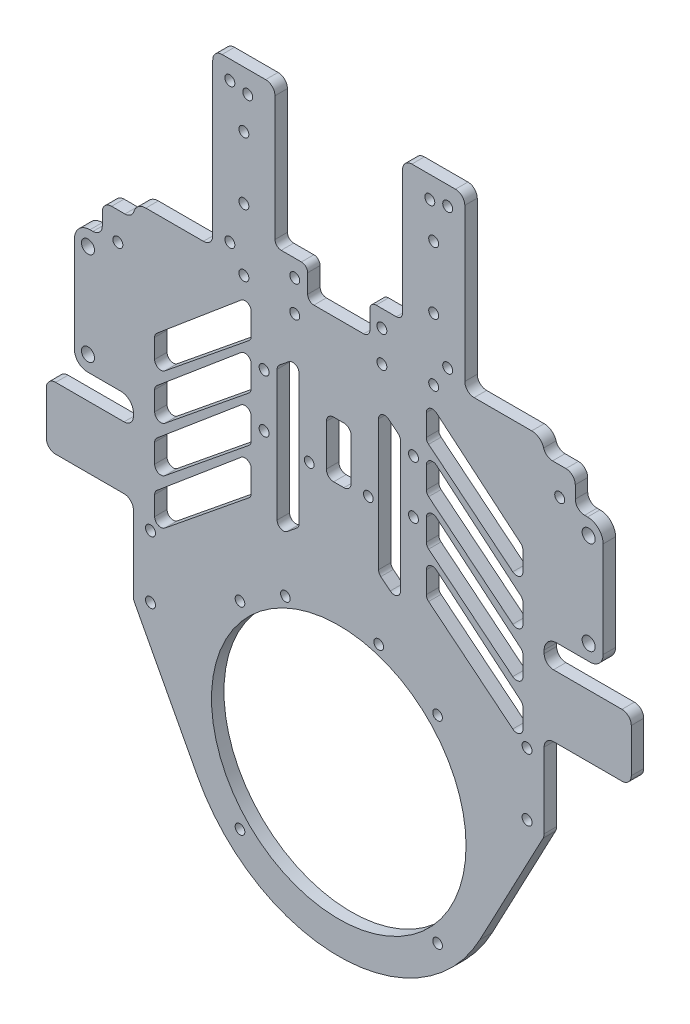
SolidWorks part; units mm, degrees
material "Thornel Mat VMA"
ref_plane "前视基准面" through (0, 0, 0) normal (0, 0, 1) x (1, 0, 0)
ref_plane "上视基准面" through (0, 0, 0) normal (0, 1, 0) x (1, 0, 0)
ref_plane "右视基准面" through (0, 0, 0) normal (1, 0, 0) x (0, 0, -1)
sketch "草图1" plane through (0, 0, 0) normal (0, 0, 1) x (1, 0, 0)
  line L0 (-66, 126) -> (66, 126)
  line L1 (66, 126) -> (66, 15.1)
  line L2 (66, 15.1) -> (45.3153, -23.9831)
  line L3 (-45.3153, -23.9831) -> (-66, 15.1)
  line L4 (-66, 15.1) -> (-66, 126)
  line L5 (0, 143.651) -> (0, -77.7988) construction
  line L6 (-17.1531, 40.4102) -> (0, 0) construction
  line L7 (0, 0) -> (12.8351, 41.9818) construction
  line L8 (-31.7491, 31.7491) -> (0, 0) construction
  line L9 (-24.2152, 81.5) -> (25.2173, 81.5) construction
  line L10 (-29.945, 120.5) -> (27.106, 120.5) construction
  arc A0 (45.3153, -23.9831) -> (-45.3153, -23.9831) centre (0, 0) cw
  circle A1 centre (0, 0) radius 40.9
  circle A2 centre (0, 0) radius 44.9 construction
  circle A3 centre (-31.7491, 31.7491) radius 1.55
  circle A4 centre (-17.1531, 40.4102) radius 1.55
  circle A5 centre (12.8351, 41.9818) radius 1.55
  circle A6 centre (31.7491, 31.7491) radius 1.55
  circle A7 centre (31.7491, -31.7491) radius 1.55
  circle A8 centre (-31.7491, -31.7491) radius 1.55
  circle A9 centre (-9.5, 81.5) radius 1.55
  circle A10 centre (9.5, 81.5) radius 1.55
  circle A11 centre (-14.15, 120.5) radius 1.6
  circle A12 centre (13.85, 120.5) radius 1.6
  point P27 (0, 0)
  dimension "D3" = 81.8
  dimension "D4" = 89.8
  dimension "D7" = 17
  dimension "D11" = 3.1
  dimension "D14" = 63.4982
  dimension "D15" = 44.9
  dimension "D17" = 9.5
  dimension "D20" = 3.2
  dimension "D21" = 14.15
  dimension "D1" = 132
  dimension "D2" = 110.9
  dimension "D5" = 126
  dimension "D6" = 152.11
  dimension "D8" = 40
  dimension "D9" = 43.9
  dimension "D10" = 43.9
  dimension "D13" = 45
  dimension "D16" = 81.5
  dimension "D18" = 9.5
  dimension "D19" = 5.5
  dimension "D22" = 13.85
  dimension "D12" = 4
extrude "凸台-拉伸1" add sketch "草图1" along normal blind 4
sketch "草图2" plane through (0, 0, 4) normal (0, 0, 1) x (1, 0, 0)
  line L0 (-66, 111) -> (-79.95, 111)
  line L1 (-66, 126) -> (-66, 15.1) construction
  line L2 (-84.95, 106) -> (-84.95, 75.2)
  line L3 (-80.75, 71) -> (-66, 71)
  line L4 (-66, 71) -> (-66, 111)
  line L5 (0, 118.3019) -> (0, -51.4362) construction
  line L6 (66, 126) -> (-66, 126) construction
  line L7 (66, 71) -> (66, 111)
  line L8 (80.75, 71) -> (66, 71)
  line L9 (84.95, 106) -> (84.95, 75.2)
  line L10 (66, 111) -> (79.95, 111)
  circle A0 centre (-80.6, 106) radius 2.1
  circle A1 centre (-80.6, 76) radius 2.1
  arc A2 (-84.95, 106) -> (-79.95, 111) centre (-79.95, 106) cw
  arc A3 (-84.95, 75.2) -> (-80.75, 71) centre (-80.75, 75.2) ccw
  arc A4 (84.95, 75.2) -> (80.75, 71) centre (80.75, 75.2) cw
  arc A5 (84.95, 106) -> (79.95, 111) centre (79.95, 106) ccw
  circle A6 centre (80.3, 76) radius 2.1
  circle A7 centre (80.3, 106) radius 2.1
  point P18 (-84.95, 111)
  point P21 (-84.95, 71)
  point P34 (84.95, 71)
  point P35 (84.95, 111)
  dimension "D3" = 4.2
  dimension "D6" = 4.35
  dimension "D9" = 5
  dimension "D10" = 4.2
  dimension "D4" = 30
  dimension "D8" = 4.35
  dimension "D12" = 30
  dimension "D13" = 5
  dimension "D14" = 4.2
  dimension "D15" = 4.2
  dimension "D16" = 4.65
  dimension "D17" = 4.65
  dimension "D2" = 40
  dimension "D5" = 5
  dimension "D7" = 15
  dimension "D11" = 169.9
extrude "凸台-拉伸2" add sketch "草图2" against normal blind 4
sketch "草图3" plane through (0, 0, 4) normal (0, 0, 1) x (1, 0, 0)
  line L0 (0, 115.5232) -> (0, -53.75) construction
  line L13 (-4, 95.6433) -> (-4, 82.3567)
  line L14 (-1.6433, 80) -> (1.6433, 80)
  line L15 (4, 82.3567) -> (4, 95.6433)
  line L16 (1.6433, 98) -> (-1.6433, 98)
  line L32 (84.95, 75.2) -> (84.95, 106) construction
  line L33 (66, 126) -> (-66, 126) construction
  line L40 (-31.4189, 115.6719) -> (-58.4619, 92.9442)
  line L41 (-59.1752, 91.4131) -> (-59.1752, 85.2814)
  line L42 (-55.9148, 83.7285) -> (-28.8718, 105.6783)
  line L43 (-28.1322, 107.2311) -> (-28.1322, 114.1408)
  line L44 (-28.1322, 92.6485) -> (-28.1322, 99.5581)
  line L45 (-31.4189, 101.0892) -> (-58.4619, 78.3615)
  line L46 (-55.9148, 69.1458) -> (-28.8718, 91.0956)
  line L47 (-59.1752, 76.8304) -> (-59.1752, 70.6987)
  line L48 (-28.1322, 78.0658) -> (-28.1322, 84.9755)
  line L49 (-31.4189, 86.5065) -> (-58.4619, 63.7788)
  line L50 (-55.9148, 54.5632) -> (-28.8718, 76.5129)
  line L51 (-59.1752, 62.2477) -> (-59.1752, 56.116)
  line L52 (-28.1322, 63.4831) -> (-28.1322, 70.3928)
  line L53 (-31.4189, 71.9239) -> (-58.4619, 49.1961)
  line L54 (-55.9148, 39.9805) -> (-28.8718, 61.9302)
  line L55 (-59.1752, 47.665) -> (-59.1752, 41.5333)
  line L56 (-16.0321, 106.2463) -> (-19.0746, 103.7769)
  line L57 (-19.8142, 102.224) -> (-19.8142, 60.2677)
  line L58 (-16.5538, 58.7148) -> (-13.5113, 61.1843)
  line L59 (-12.7717, 62.7371) -> (-12.7717, 104.6934)
  line L60 (12.7717, 62.7371) -> (12.7717, 104.6934)
  line L61 (16.5538, 58.7148) -> (13.5113, 61.1843)
  line L62 (19.8142, 102.224) -> (19.8142, 60.2677)
  line L63 (16.0321, 106.2463) -> (19.0746, 103.7769)
  line L64 (59.1752, 47.665) -> (59.1752, 41.5333)
  line L65 (55.9148, 39.9805) -> (28.8718, 61.9302)
  line L66 (31.4189, 71.9239) -> (58.4619, 49.1961)
  line L67 (28.1322, 63.4831) -> (28.1322, 70.3928)
  line L68 (59.1752, 62.2477) -> (59.1752, 56.116)
  line L69 (55.9148, 54.5632) -> (28.8718, 76.5129)
  line L70 (31.4189, 86.5065) -> (58.4619, 63.7788)
  line L71 (28.1322, 78.0658) -> (28.1322, 84.9755)
  line L72 (59.1752, 76.8304) -> (59.1752, 70.6987)
  line L73 (55.9148, 69.1458) -> (28.8718, 91.0956)
  line L74 (31.4189, 101.0892) -> (58.4619, 78.3615)
  line L75 (28.1322, 92.6485) -> (28.1322, 99.5581)
  line L76 (28.1322, 107.2311) -> (28.1322, 114.1408)
  line L77 (55.9148, 83.7285) -> (28.8718, 105.6783)
  line L78 (59.1752, 91.4131) -> (59.1752, 85.2814)
  line L79 (31.4189, 115.6719) -> (58.4619, 92.9442)
  circle A9 centre (0, 0) radius 40.9 construction
  arc A10 (4, 95.6433) -> (1.6433, 98) centre (1.6433, 95.6433) ccw
  arc A11 (4, 82.3567) -> (1.6433, 80) centre (1.6433, 82.3567) cw
  arc A12 (-1.6433, 80) -> (-4, 82.3567) centre (-1.6433, 82.3567) cw
  arc A13 (-4, 95.6433) -> (-1.6433, 98) centre (-1.6433, 95.6433) cw
  arc A35 (-16.0321, 106.2463) -> (-12.7717, 104.6934) centre (-14.7717, 104.6934) cw
  arc A36 (-19.0746, 103.7769) -> (-19.8142, 102.224) centre (-17.8142, 102.224) ccw
  arc A37 (-13.5113, 61.1843) -> (-12.7717, 62.7371) centre (-14.7717, 62.7371) ccw
  arc A38 (-19.8142, 60.2677) -> (-16.5538, 58.7148) centre (-17.8142, 60.2677) ccw
  arc A39 (-55.9148, 39.9805) -> (-59.1752, 41.5333) centre (-57.1752, 41.5333) cw
  arc A40 (-58.4619, 49.1961) -> (-59.1752, 47.665) centre (-57.1752, 47.665) ccw
  arc A41 (-28.1322, 63.4831) -> (-28.8718, 61.9302) centre (-30.1322, 63.4831) cw
  arc A42 (-28.1322, 70.3928) -> (-31.4189, 71.9239) centre (-30.1322, 70.3928) ccw
  arc A43 (-55.9148, 54.5632) -> (-59.1752, 56.116) centre (-57.1752, 56.116) cw
  arc A44 (-58.4619, 63.7788) -> (-59.1752, 62.2477) centre (-57.1752, 62.2477) ccw
  arc A45 (-28.1322, 78.0658) -> (-28.8718, 76.5129) centre (-30.1322, 78.0658) cw
  arc A46 (-28.1322, 84.9755) -> (-31.4189, 86.5065) centre (-30.1322, 84.9755) ccw
  arc A47 (-58.4619, 78.3615) -> (-59.1752, 76.8304) centre (-57.1752, 76.8304) ccw
  arc A48 (-55.9148, 69.1458) -> (-59.1752, 70.6987) centre (-57.1752, 70.6987) cw
  arc A49 (-28.1322, 92.6485) -> (-28.8718, 91.0956) centre (-30.1322, 92.6485) cw
  arc A50 (-28.1322, 99.5581) -> (-31.4189, 101.0892) centre (-30.1322, 99.5581) ccw
  arc A51 (-59.1752, 85.2814) -> (-55.9148, 83.7285) centre (-57.1752, 85.2814) ccw
  arc A52 (-58.4619, 92.9442) -> (-59.1752, 91.4131) centre (-57.1752, 91.4131) ccw
  arc A53 (-28.8718, 105.6783) -> (-28.1322, 107.2311) centre (-30.1322, 107.2311) ccw
  arc A54 (-31.4189, 115.6719) -> (-28.1322, 114.1408) centre (-30.1322, 114.1408) cw
  arc A55 (31.4189, 115.6719) -> (28.1322, 114.1408) centre (30.1322, 114.1408) ccw
  arc A56 (28.8718, 105.6783) -> (28.1322, 107.2311) centre (30.1322, 107.2311) cw
  arc A57 (58.4619, 92.9442) -> (59.1752, 91.4131) centre (57.1752, 91.4131) cw
  arc A58 (59.1752, 85.2814) -> (55.9148, 83.7285) centre (57.1752, 85.2814) cw
  arc A59 (28.1322, 99.5581) -> (31.4189, 101.0892) centre (30.1322, 99.5581) cw
  arc A60 (28.1322, 92.6485) -> (28.8718, 91.0956) centre (30.1322, 92.6485) ccw
  arc A61 (55.9148, 69.1458) -> (59.1752, 70.6987) centre (57.1752, 70.6987) ccw
  arc A62 (58.4619, 78.3615) -> (59.1752, 76.8304) centre (57.1752, 76.8304) cw
  arc A63 (28.1322, 84.9755) -> (31.4189, 86.5065) centre (30.1322, 84.9755) cw
  arc A64 (28.1322, 78.0658) -> (28.8718, 76.5129) centre (30.1322, 78.0658) ccw
  arc A65 (58.4619, 63.7788) -> (59.1752, 62.2477) centre (57.1752, 62.2477) cw
  arc A66 (55.9148, 54.5632) -> (59.1752, 56.116) centre (57.1752, 56.116) ccw
  arc A67 (28.1322, 70.3928) -> (31.4189, 71.9239) centre (30.1322, 70.3928) cw
  arc A68 (28.1322, 63.4831) -> (28.8718, 61.9302) centre (30.1322, 63.4831) ccw
  arc A69 (58.4619, 49.1961) -> (59.1752, 47.665) centre (57.1752, 47.665) cw
  arc A70 (55.9148, 39.9805) -> (59.1752, 41.5333) centre (57.1752, 41.5333) ccw
  arc A71 (19.8142, 60.2677) -> (16.5538, 58.7148) centre (17.8142, 60.2677) cw
  arc A72 (13.5113, 61.1843) -> (12.7717, 62.7371) centre (14.7717, 62.7371) cw
  arc A73 (19.0746, 103.7769) -> (19.8142, 102.224) centre (17.8142, 102.224) cw
  arc A74 (16.0321, 106.2463) -> (12.7717, 104.6934) centre (14.7717, 104.6934) ccw
  dimension "D1" = 4
  dimension "D6" = 2.3567
  dimension "D7" = 2
  dimension "D2" = 4
  dimension "D3" = 4
  dimension "D4" = 18
  dimension "D5" = 80
extrude "切除-拉伸1" cut sketch "草图3" against normal blind 4
fillet "圆角1" radius 4 4 edges at (-66, 71, 2) (66, 71, 2) (66, 126, 2) (-66, 126, 2)
sketch "草图4" plane through (0, 0, 4) normal (0, 0, 1) x (1, 0, 0)
  line L0 (-10, 126) -> (-10, 119)
  line L1 (62, 126) -> (-62, 126) construction
  line L2 (-10, 119) -> (10, 119)
  line L3 (10, 119) -> (10, 126)
  line L4 (10, 126) -> (-10, 126)
  line L5 (66, 111) -> (66, 122) construction
  dimension "D1" = 7
  dimension "D2" = 20
  dimension "D3" = 56
extrude "切除-拉伸2" cut sketch "草图4" against normal through all
fillet "圆角2" radius 2 4 edges at (10, 126, 2) (-10, 126, 2) (-10, 119, 2) (10, 119, 2)
sketch "草图5" plane through (0, 0, 4) normal (0, 0, 1) x (1, 0, 0)
  line L0 (-40.5, 126) -> (-40.5, 181)
  line L1 (-12, 126) -> (-62, 126) construction
  line L2 (-40.5, 181) -> (-20.5, 181)
  line L3 (-20.5, 181) -> (-20.5, 126)
  line L4 (-40.5, 126) -> (-20.5, 126)
  line L5 (0, 172.5721) -> (0, 103.5745) construction
  line L10 (20.5, 126) -> (20.5, 181)
  line L11 (62, 126) -> (12, 126) construction
  line L12 (20.5, 181) -> (40.5, 181)
  line L13 (40.5, 181) -> (40.5, 126)
  line L14 (40.5, 126) -> (20.5, 126)
  dimension "D1" = 20
  dimension "D2" = 55
  dimension "D3" = 20.5
  dimension "D4" = 20
  dimension "D5" = 55
  dimension "D6" = 20.5
extrude "凸台-拉伸3" add sketch "草图5" against normal blind 4
sketch "草图6" plane through (0, 0, 4) normal (0, 0, 1) x (1, 0, 0)
  line L0 (-40.5, 181) -> (-40.5, 126) construction
  line L2 (0, 181.9353) -> (0, 128.2449) construction
  line L3 (-20.5, 181) -> (-40.5, 181) construction
  circle A0 centre (-29.75, 177) radius 1.65
  circle A1 centre (-29.75, 143.5) radius 1.65
  circle A4 centre (29.75, 143.5) radius 1.65
  circle A5 centre (29.75, 177) radius 1.65
  dimension "D1" = 3.3
  dimension "D2" = 10.75
  dimension "D4" = 4
  dimension "D3" = 33.5
fillet "圆角3" radius 3 4 edges at (40.5, 126, 2) (40.5, 181, 2) (-40.5, 126, 2) (-40.5, 181, 2)
sketch "草图7" plane through (0, 0, 4) normal (0, 0, 1) x (1, 0, 0)
  line L0 (0, 0) -> (0, 119) construction
  line L1 (-8, 119) -> (8, 119) construction
  line L2 (-30.5, 163) -> (-30.5, 130.7752) construction
  line L5 (-43.5, 126) -> (-62, 126) construction
  circle A0 centre (-30.5, 163) radius 1.6
  circle A1 centre (-30.5, 143) radius 1.6
  circle A2 centre (-30.5, 123) radius 1.6
  circle A3 centre (30.5, 163) radius 1.6
  circle A4 centre (30.5, 123) radius 1.6
  circle A5 centre (30.5, 143) radius 1.6
  dimension "D1" = 3.2
  dimension "D2" = 20
  dimension "D3" = 20
  dimension "D4" = 61
  dimension "D5" = 3
extrude "切除-拉伸4" cut sketch "草图7" against normal blind 10
sketch "草图8" plane through (0, 0, 4) normal (0, 0, 1) x (1, 0, 0)
  line L2 (24, 83) -> (-24, 83) construction
  line L3 (24, 83) -> (24, 100) construction
  line L4 (24, 100) -> (-24, 100) construction
  line L5 (-24, 83) -> (-24, 100) construction
  line L6 (24, 83) -> (-24, 100) construction
  line L7 (24, 100) -> (-24, 83) construction
  line L8 (37.5, 181) -> (20.5, 181) construction
  line L9 (0, 0) -> (0, 123.2843)
  circle A0 centre (-24, 100) radius 1.6
  circle A1 centre (24, 100) radius 1.6
  circle A2 centre (24, 83) radius 1.6
  circle A3 centre (-24, 83) radius 1.6
  point P0 (0, 91.5)
  dimension "D1" = 17
  dimension "D2" = 48
  dimension "D4" = 3.2
  dimension "D3" = 81
extrude "切除-拉伸7" cut sketch "草图8" against normal blind 24 contours A0 | A3 | A2 | A1
sketch "草图9" plane through (0, 0, 4) normal (0, 0, 1) x (1, 0, 0)
  line L0 (0, 0) -> (0, 119) construction
  line L1 (66, 111) -> (76, 111)
  line L2 (66, 111) -> (66, 121)
  line L3 (66, 121) -> (76, 121)
  line L4 (76, 111) -> (76, 121)
  line L5 (-8, 119) -> (8, 119) construction
  line L6 (-66, 121) -> (-76, 121)
  line L7 (-76, 111) -> (-76, 121)
  line L8 (-66, 111) -> (-76, 111)
  line L9 (-66, 111) -> (-66, 121)
  dimension "D1" = 10
  dimension "D2" = 10
extrude "凸台-拉伸4" add sketch "草图9" against normal blind 4
fillet "圆角5" radius 3 6 edges at (-76, 111, 2) (-76, 121, 2) (-66, 121, 2) (66, 121, 2) (76, 121, 2) (76, 111, 2)
sketch "草图10" plane through (0, 0, 4) normal (0, 0, 1) x (1, 0, 0)
  line L0 (-76, 118) -> (-76, 114) construction
  line L1 (-68.7082, 121) -> (-73, 121) construction
  line L2 (0, 0) -> (0, 119) construction
  line L3 (-8, 119) -> (8, 119) construction
  circle A0 centre (-71, 112) radius 1.6
  circle A1 centre (71, 112) radius 1.6
  dimension "D1" = 3.2
  dimension "D2" = 5
  dimension "D3" = 9
extrude "切除-拉伸6" cut sketch "草图10" against normal blind 4
sketch "草图11" plane through (0, 0, 4) normal (0, 0, 1) x (1, 0, 0)
  line L0 (66, 15.1) -> (66, 67) construction
  line L1 (66, 63) -> (94, 63)
  line L2 (66, 63) -> (66, 43)
  line L3 (66, 43) -> (94, 43)
  line L4 (94, 63) -> (94, 43)
  line L5 (70, 71) -> (80.75, 71) construction
  line L6 (0, 27.3868) -> (0, -17.8221) construction
  line L7 (-66, 43) -> (-94, 43)
  line L8 (-66, 63) -> (-66, 43)
  line L9 (-66, 63) -> (-94, 63)
  line L10 (-94, 63) -> (-94, 43)
  dimension "D1" = 20
  dimension "D2" = 28
  dimension "D3" = 8
extrude "凸台-拉伸5" add sketch "草图11" against normal blind 4
fillet "圆角6" radius 3 12 edges at (-20.5, 181, 2) (20.5, 181, 2) (-94, 63, 2) (-94, 43, 2) (-66, 43, 2) (-66, 15.1, 2) (66, 15.1, 2) (66, 43, 2) (94, 43, 2) (94, 63, 2) (66, 63, 2) (-66, 63, 2)
sketch "草图13" plane through (0, 0, 4) normal (0, 0, 1) x (1, 0, 0)
  line L0 (-60.5, 152.6337) -> (-60.5, -37.2841) construction
  line L1 (-66, 40) -> (-66, 15.8449) construction
  line L2 (-91, 43) -> (-69, 43) construction
  line L3 (0, 166.4374) -> (0, -97.031) construction
  circle A0 centre (-60.5, 37) radius 1.6
  circle A1 centre (-60.5, 17) radius 1.6
  circle A2 centre (60.5, 17) radius 1.6
  circle A3 centre (60.5, 37) radius 1.6
  dimension "D2" = 3.2
  dimension "D3" = 20
  dimension "D4" = 6
  dimension "D1" = 5.5
extrude "切除-拉伸8" cut sketch "草图13" against normal blind 45
sketch "草图14" plane through (0, 0, 4) normal (0, 0, 1) x (1, 0, 0)
  line L0 (-23.5, 181) -> (-37.5, 181) construction
  line L1 (-40.5, 178) -> (-40.5, 129) construction
  line L2 (0, 181.7466) -> (0, 80.6903) construction
  circle A0 centre (-29.25, 174) radius 1.6
  circle A1 centre (29.25, 174) radius 1.6
  dimension "D1" = 3.2
  dimension "D2" = 7
  dimension "D3" = 11.25
extrude "切除-拉伸9" cut sketch "草图14" against normal blind 10
sketch "草图15" plane through (0, 0, 4) normal (0, 0, 1) x (1, 0, 0)
  line L0 (0, 152.5) -> (0, 0) construction
  line L1 (35, 130) -> (-35, 130) construction
  line L2 (35, 130) -> (35, 175) construction
  line L3 (35, 175) -> (-35, 175) construction
  line L4 (-35, 130) -> (-35, 175) construction
  line L5 (35, 130) -> (-35, 175) construction
  line L6 (35, 175) -> (-35, 130) construction
  line L7 (-23.5, 181) -> (-37.5, 181) construction
  circle A0 centre (-35, 175) radius 1.6
  circle A1 centre (35, 175) radius 1.6
  circle A2 centre (-35, 130) radius 1.6
  circle A3 centre (35, 130) radius 1.6
  point P0 (0, 152.5)
  dimension "D4" = 3.2
  dimension "D1" = 45
  dimension "D2" = 70
  dimension "D3" = 6
extrude "切除-拉伸10" cut sketch "草图15" against normal blind 10
sketch "草图16" plane through (0, 0, 4) normal (0, 0, 1) x (1, 0, 0)
  line L0 (-20.5, 136) -> (20.5, 136)
  line L1 (-14.15, 130.5) -> (-14.15, 120.5) construction
  line L2 (13.85, 120.5) -> (13.85, 130.5) construction
  line L35 (-20.5, 126) -> (-20.5, 178)
  line L36 (-23.5, 181) -> (-37.5, 181)
  line L37 (-40.5, 178) -> (-40.5, 129)
  line L38 (-43.5, 126) -> (-62, 126)
  line L39 (-68.7082, 121) -> (-73, 121)
  line L40 (-76, 118) -> (-76, 114)
  line L41 (-79, 111) -> (-79.95, 111)
  line L42 (-84.95, 106) -> (-84.95, 75.2)
  line L43 (-80.75, 71) -> (-70, 71)
  line L44 (-66, 67) -> (-66, 66)
  line L45 (-69, 63) -> (-91, 63)
  line L46 (-94, 60) -> (-94, 46)
  line L47 (-91, 43) -> (-69, 43)
  line L48 (-66, 40) -> (-66, 15.8449)
  line L49 (-65.6515, 14.4416) -> (-45.3153, -23.9831)
  line L50 (45.3153, -23.9831) -> (65.6515, 14.4416)
  line L51 (66, 15.8449) -> (66, 40)
  line L52 (69, 43) -> (91, 43)
  line L53 (94, 46) -> (94, 60)
  line L54 (91, 63) -> (69, 63)
  line L55 (66, 66) -> (66, 67)
  line L56 (70, 71) -> (80.75, 71)
  line L57 (84.95, 75.2) -> (84.95, 106)
  line L58 (79.95, 111) -> (79, 111)
  line L59 (76, 114) -> (76, 118)
  line L60 (73, 121) -> (68.7082, 121)
  line L61 (62, 126) -> (43.5, 126)
  line L62 (40.5, 129) -> (40.5, 178)
  line L63 (37.5, 181) -> (23.5, 181)
  line L64 (20.5, 178) -> (20.5, 126)
  line L65 (20.5, 126) -> (12, 126)
  line L66 (10, 124) -> (10, 121)
  line L67 (8, 119) -> (-8, 119)
  line L68 (-10, 121) -> (-10, 124)
  line L69 (-12, 126) -> (-20.5, 126)
  line L70 (-20.5, 126) -> (-20.5, 136)
  line L99 (20.5, 136) -> (20.5, 126)
  line L100 (20.5, 126) -> (12, 126)
  line L101 (10, 124) -> (10, 121)
  line L102 (8, 119) -> (-8, 119)
  line L103 (-10, 121) -> (-10, 124)
  line L104 (-12, 126) -> (-20.5, 126)
  circle A0 centre (-14.15, 130.5) radius 1.6
  circle A1 centre (13.85, 130.5) radius 1.6
  arc A35 (-20.5, 178) -> (-23.5, 181) centre (-23.5, 178) ccw
  arc A36 (-37.5, 181) -> (-40.5, 178) centre (-37.5, 178) ccw
  arc A37 (-43.5, 126) -> (-40.5, 129) centre (-43.5, 129) ccw
  arc A38 (-62, 126) -> (-65.8333, 123.1429) centre (-62, 122) ccw
  arc A39 (-68.7082, 121) -> (-65.8333, 123.1429) centre (-68.7082, 124) ccw
  arc A40 (-73, 121) -> (-76, 118) centre (-73, 118) ccw
  arc A41 (-79, 111) -> (-76, 114) centre (-79, 114) ccw
  arc A42 (-79.95, 111) -> (-84.95, 106) centre (-79.95, 106) ccw
  arc A43 (-84.95, 75.2) -> (-80.75, 71) centre (-80.75, 75.2) ccw
  arc A44 (-66, 67) -> (-70, 71) centre (-70, 67) ccw
  arc A45 (-69, 63) -> (-66, 66) centre (-69, 66) ccw
  arc A46 (-91, 63) -> (-94, 60) centre (-91, 60) ccw
  arc A47 (-94, 46) -> (-91, 43) centre (-91, 46) ccw
  arc A48 (-66, 40) -> (-69, 43) centre (-69, 40) ccw
  arc A49 (-66, 15.8449) -> (-65.6515, 14.4416) centre (-63, 15.8449) ccw
  arc A50 (-45.3153, -23.9831) -> (45.3153, -23.9831) centre (0, 0) ccw
  arc A51 (65.6515, 14.4416) -> (66, 15.8449) centre (63, 15.8449) ccw
  arc A52 (69, 43) -> (66, 40) centre (69, 40) ccw
  arc A53 (91, 43) -> (94, 46) centre (91, 46) ccw
  arc A54 (94, 60) -> (91, 63) centre (91, 60) ccw
  arc A55 (66, 66) -> (69, 63) centre (69, 66) ccw
  arc A56 (70, 71) -> (66, 67) centre (70, 67) ccw
  arc A57 (80.75, 71) -> (84.95, 75.2) centre (80.75, 75.2) ccw
  arc A58 (84.95, 106) -> (79.95, 111) centre (79.95, 106) ccw
  arc A59 (76, 114) -> (79, 111) centre (79, 114) ccw
  arc A60 (76, 118) -> (73, 121) centre (73, 118) ccw
  arc A61 (65.8333, 123.1429) -> (68.7082, 121) centre (68.7082, 124) ccw
  arc A62 (65.8333, 123.1429) -> (62, 126) centre (62, 122) ccw
  arc A63 (40.5, 129) -> (43.5, 126) centre (43.5, 129) ccw
  arc A64 (40.5, 178) -> (37.5, 181) centre (37.5, 178) ccw
  arc A65 (23.5, 181) -> (20.5, 178) centre (23.5, 178) ccw
  arc A66 (12, 126) -> (10, 124) centre (12, 124) ccw
  arc A67 (8, 119) -> (10, 121) centre (8, 121) ccw
  arc A68 (-10, 121) -> (-8, 119) centre (-8, 121) ccw
  arc A69 (-10, 124) -> (-12, 126) centre (-12, 124) ccw
  arc A101 (12, 126) -> (10, 124) centre (12, 124) ccw
  arc A102 (8, 119) -> (10, 121) centre (8, 121) ccw
  arc A103 (-10, 121) -> (-8, 119) centre (-8, 121) ccw
  arc A104 (-10, 124) -> (-12, 126) centre (-12, 124) ccw
  dimension "D3" = 3.2
  dimension "D4" = 3.2
  dimension "D5" = 10
  dimension "D2" = 17
  dimension "D6" = 10
  dimension "D1" = 0
extrude "凸台-拉伸6" add sketch "草图16" against normal blind 4
sketch "草图17" plane through (0, 0, 4) normal (0, 0, 1) x (1, 0, 0)
  line L0 (20.5, 136) -> (-20.5, 136) construction
  line L1 (10, 126) -> (-10, 126)
  line L2 (10, 126) -> (10, 136)
  line L3 (10, 136) -> (-10, 136)
  line L4 (-10, 126) -> (-10, 136)
  dimension "D1" = 20
  dimension "D2" = 10
  dimension "D3" = 10
extrude "切除-拉伸11" cut sketch "草图17" against normal blind 4
fillet "圆角7" radius 2 6 edges at (10, 126, 2) (-10, 126, 2) (-10, 136, 2) (20.5, 136, 2) (10, 136, 2) (-20.5, 136, 2)
